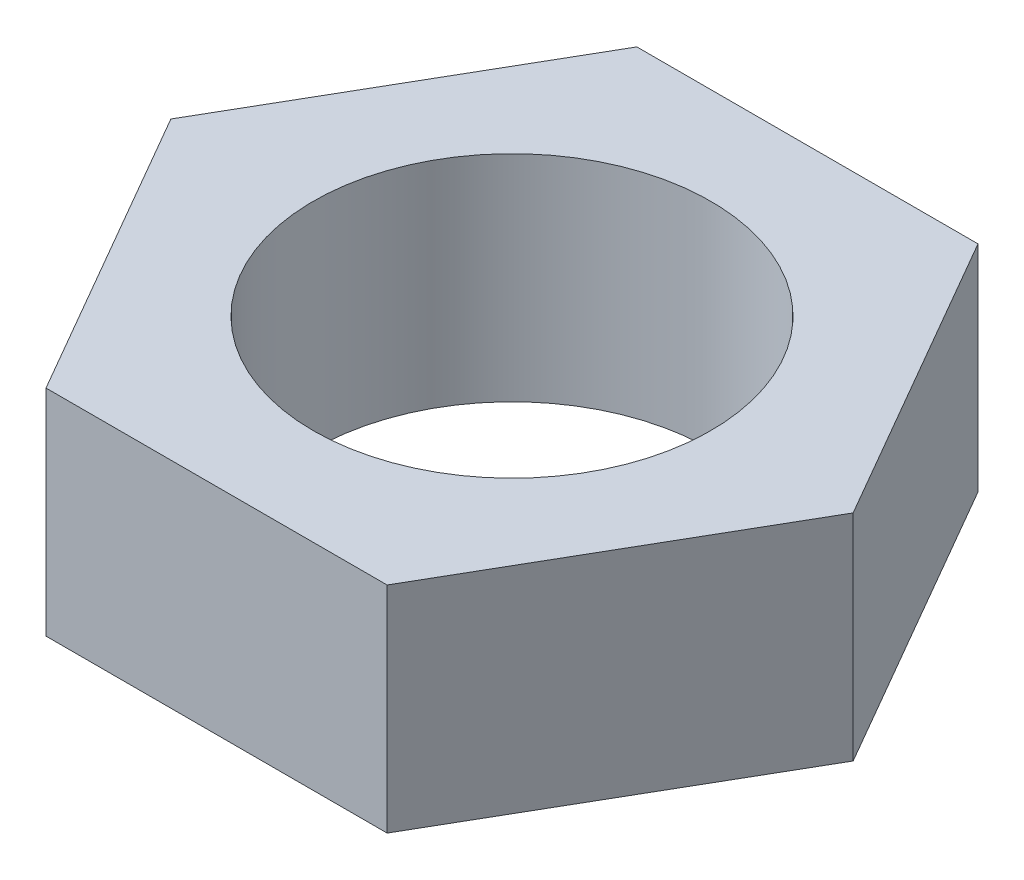
SolidWorks part; units mm, degrees
ref_plane "Front Plane" through (0, 0, 0) normal (0, 0, 1) x (1, 0, 0)
ref_plane "Top Plane" through (0, 0, 0) normal (0, 1, 0) x (1, 0, 0)
ref_plane "Right Plane" through (0, 0, 0) normal (1, 0, 0) x (0, 0, -1)
sketch "Sketch1" plane through (0, 0, 0) normal (0, 1, 0) x (1, 0, 0)
  line L1 (3.1754, 0) -> (1.5877, 2.75)
  line L2 (1.5877, 2.75) -> (-1.5877, 2.75)
  line L3 (-1.5877, 2.75) -> (-3.1754, 0)
  line L4 (-3.1754, 0) -> (-1.5877, -2.75)
  line L5 (-1.5877, -2.75) -> (1.5877, -2.75)
  line L6 (1.5877, -2.75) -> (3.1754, 0)
  circle A0 centre (0, 0) radius 2.75 construction
  circle A1 centre (0, 0) radius 1.85
  dimension "D1" = 5.5
  dimension "D2" = 3.7
extrude "Boss-Extrude1" add sketch "Sketch1" along normal blind 2
